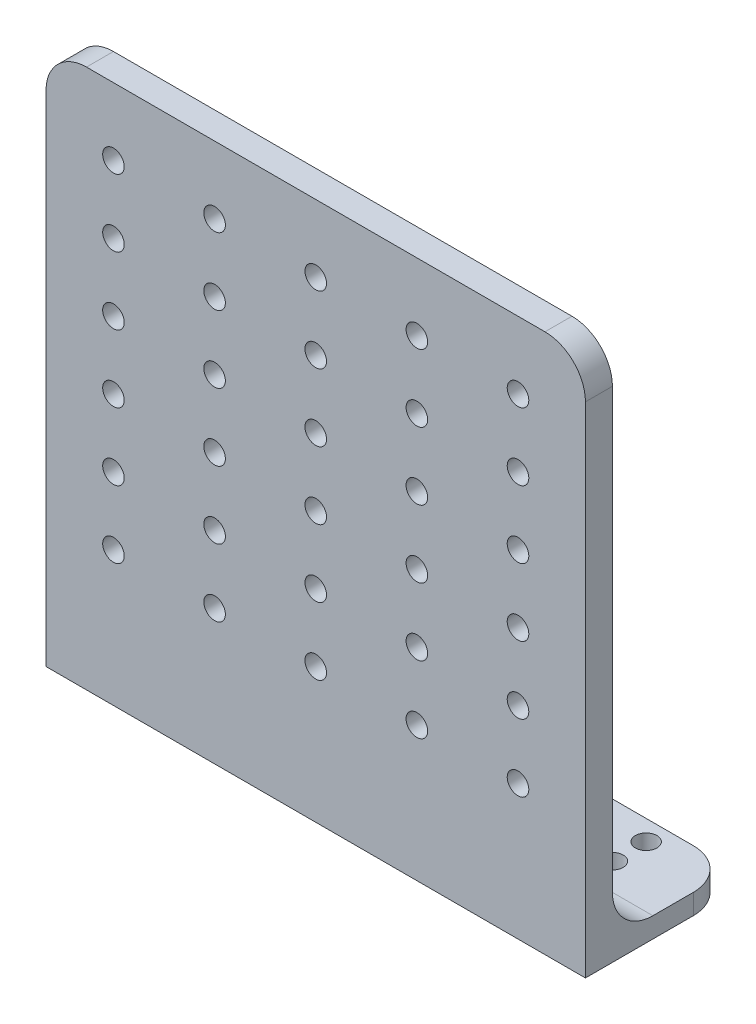
SolidWorks part; units mm, degrees
ref_plane "Front Plane" through (0, 0, 0) normal (0, 0, 1) x (1, 0, 0)
ref_plane "Top Plane" through (0, 0, 0) normal (0, 1, 0) x (1, 0, 0)
ref_plane "Right Plane" through (0, 0, 0) normal (1, 0, 0) x (0, 0, -1)
sketch "Sketch1" plane through (0, 0, 0) normal (0, 0, 1) x (1, 0, 0)
  line L1 (0, 0) -> (80, 0)
  line L2 (0, 0) -> (0, 80)
  line L3 (0, 80) -> (80, 80)
  line L4 (80, 0) -> (80, 80)
  dimension "D1" = 80
  dimension "D2" = 80
extrude "Boss-Extrude1" add sketch "Sketch1" along normal blind 4
sketch "Sketch2" plane through (0, 0, 4) normal (0, 0, 1) x (1, 0, 0)
  line L0 (10, 70) -> (25, 70) construction
  line L1 (25, 70) -> (40, 70) construction
  line L2 (40, 70) -> (55, 70) construction
  line L3 (55, 70) -> (70, 70) construction
  line L4 (80, 80) -> (0, 80) construction
  circle A0 centre (10, 70) radius 1.6
  circle A1 centre (25, 70) radius 1.6
  circle A2 centre (40, 70) radius 1.6
  circle A3 centre (55, 70) radius 1.6
  circle A4 centre (70, 70) radius 1.6
  point P12 (40, 80)
  dimension "D1" = 3.2
  dimension "D2" = 15
  dimension "D3" = 10
extrude "Cut-Extrude1" cut sketch "Sketch2" against normal through all
pattern_linear "LPattern1" count 6 spacing 10 along (0, -1, 0) of "Cut-Extrude1"
sketch "Sketch3" plane through (0, 0, 0) normal (0, 0, -1) x (-1, 0, 0)
  line L0 (-80, 0) -> (-80, 80) construction
  line L1 (-80, 3) -> (0, 3)
  line L2 (-80, 3) -> (-80, 0)
  line L3 (-80, 0) -> (0, 0)
  line L4 (0, 3) -> (0, 0)
  dimension "D1" = 3
extrude "Boss-Extrude2" add sketch "Sketch3" along normal blind 18
sketch "Sketch4" plane through (0, 3, 0) normal (0, 1, 0) x (1, 0, 0)
  line L0 (70, 15) -> (55, 15) construction
  line L1 (55, 15) -> (40, 15) construction
  line L2 (40, 15) -> (25, 15) construction
  line L3 (25, 15) -> (10, 15) construction
  line L4 (0, 18) -> (80, 18) construction
  circle A0 centre (70, 15) radius 1.6
  circle A1 centre (55, 15) radius 1.6
  circle A2 centre (40, 15) radius 1.6
  circle A3 centre (25, 15) radius 1.6
  circle A4 centre (10, 15) radius 1.6
  point P12 (40, 18)
  dimension "D1" = 3.2
  dimension "D2" = 15
  dimension "D3" = 3
extrude "Cut-Extrude2" cut sketch "Sketch4" against normal through all
pattern_linear "LPattern2" count 2 spacing 5 along (0, 0, 1) of "Cut-Extrude2"
fillet "Fillet1" radius 6 1 edges at (40, 3, 0)
fillet "Fillet2" radius 6 4 edges at (80, 80, 2) (0, 80, 2) (0, 1.5, -18) (80, 1.5, -18)
